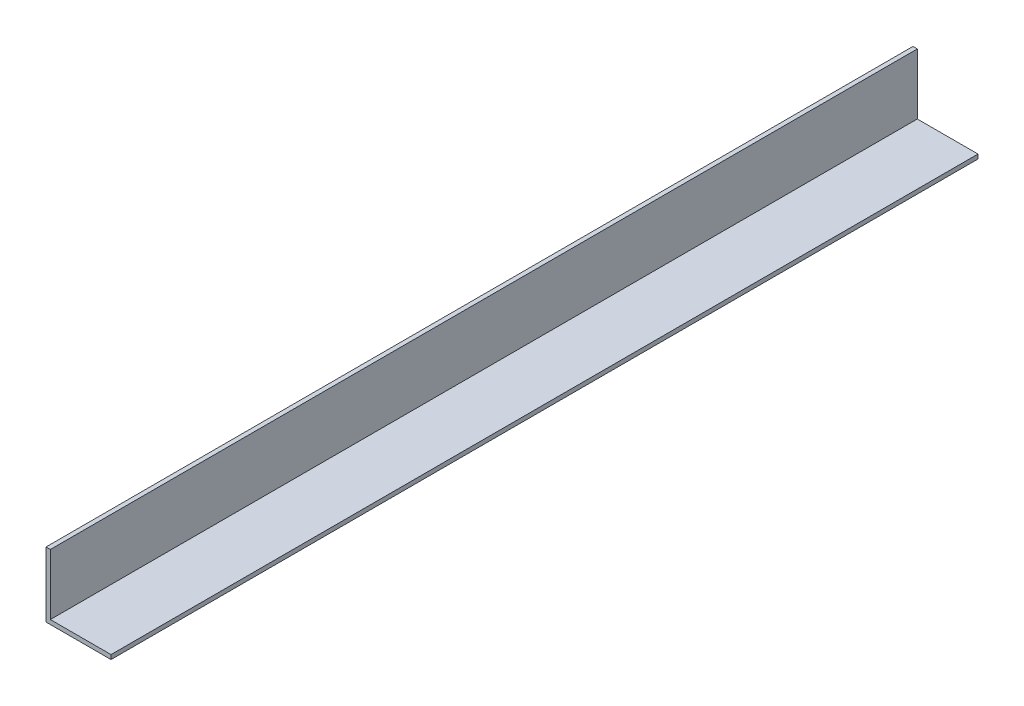
SolidWorks part; units mm, degrees
material "1060 Alloy"
ref_plane "Front Plane" through (0, 0, 0) normal (0, 0, 1) x (1, 0, 0)
ref_plane "Top Plane" through (0, 0, 0) normal (0, 1, 0) x (1, 0, 0)
ref_plane "Right Plane" through (0, 0, 0) normal (1, 0, 0) x (0, 0, -1)
sketch "Sketch1" plane through (0, 0, 0) normal (0, 0, 1) x (1, 0, 0)
  line L0 (0, 5.6023) -> (0, 35.6023)
  line L1 (0, 35.6023) -> (2, 35.6023)
  line L2 (2, 35.6023) -> (2, 7.6023)
  line L3 (2, 7.6023) -> (30, 7.6023)
  line L4 (30, 7.6023) -> (30, 5.6023)
  line L5 (30, 5.6023) -> (0, 5.6023)
extrude "Boss-Extrude1" add sketch "Sketch1" along normal blind 400
